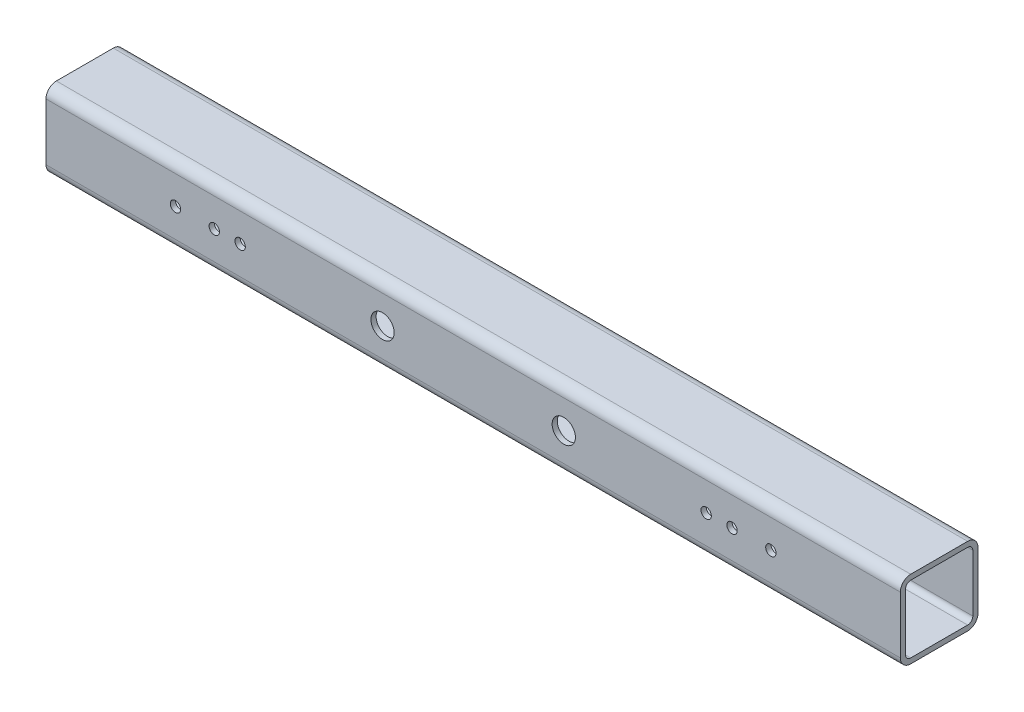
SolidWorks part; units mm, degrees
material "AISI 1010 钢，热轧条材"
ref_plane "前视基准面" through (0, 0, 0) normal (0, 0, 1) x (1, 0, 0)
ref_plane "上视基准面" through (0, 0, 0) normal (0, 1, 0) x (1, 0, 0)
ref_plane "右视基准面" through (0, 0, 0) normal (1, 0, 0) x (0, 0, -1)
sketch "草图1" plane through (0, 0, 0) normal (1, 0, 0) x (0, 0, -1)
  line L0 (4, 2) -> (26, 2)
  line L1 (4, 0) -> (26, 0)
  line L2 (0, 4) -> (0, 26)
  line L3 (4, 30) -> (26, 30)
  line L4 (30, 4) -> (30, 26)
  line L5 (28, 4) -> (28, 26)
  line L6 (4, 28) -> (26, 28)
  line L7 (2, 4) -> (2, 26)
  arc A0 (4, 0) -> (0, 4) centre (4, 4) cw
  arc A1 (26, 0) -> (30, 4) centre (26, 4) ccw
  arc A2 (26, 30) -> (30, 26) centre (26, 26) cw
  arc A3 (0, 26) -> (4, 30) centre (4, 26) cw
  arc A4 (26, 2) -> (28, 4) centre (26, 4) ccw
  arc A5 (26, 28) -> (28, 26) centre (26, 26) cw
  arc A6 (2, 26) -> (4, 28) centre (4, 26) cw
  arc A7 (4, 2) -> (2, 4) centre (4, 4) cw
  point P7 (0, 0)
  point P10 (30, 0)
  point P13 (30, 30)
  point P16 (0, 30)
  dimension "D3" = 4
  dimension "D1" = 30
  dimension "D2" = 30
  dimension "D4" = 2
extrude "凸台-拉伸1" add sketch "草图1" along normal mid plane 330
sketch "草图2" plane through (0, 0, 0) normal (0, 0, 1) x (1, 0, 0)
  line L0 (0, 0) -> (0, 30) construction
  line L1 (165, 30) -> (-165, 30) construction
  line L2 (-165, 26) -> (-165, 4) construction
  circle A0 centre (-35, 15) radius 4.5
  circle A1 centre (35, 15) radius 4.5
  circle A2 centre (-115, 15) radius 2
  circle A3 centre (115, 15) radius 2
  circle A4 centre (-100, 15) radius 2
  circle A5 centre (-90, 15) radius 2
  circle A6 centre (90, 15) radius 2
  circle A7 centre (100, 15) radius 2
  point P13 (-165, 15)
  point P20 (0, 0)
  dimension "D1" = 9
  dimension "D3" = 4
  dimension "D2" = 70
  dimension "D4" = 50
  dimension "D5" = 10
  dimension "D6" = 90
extrude "切除-拉伸1" cut sketch "草图2" against normal through all
